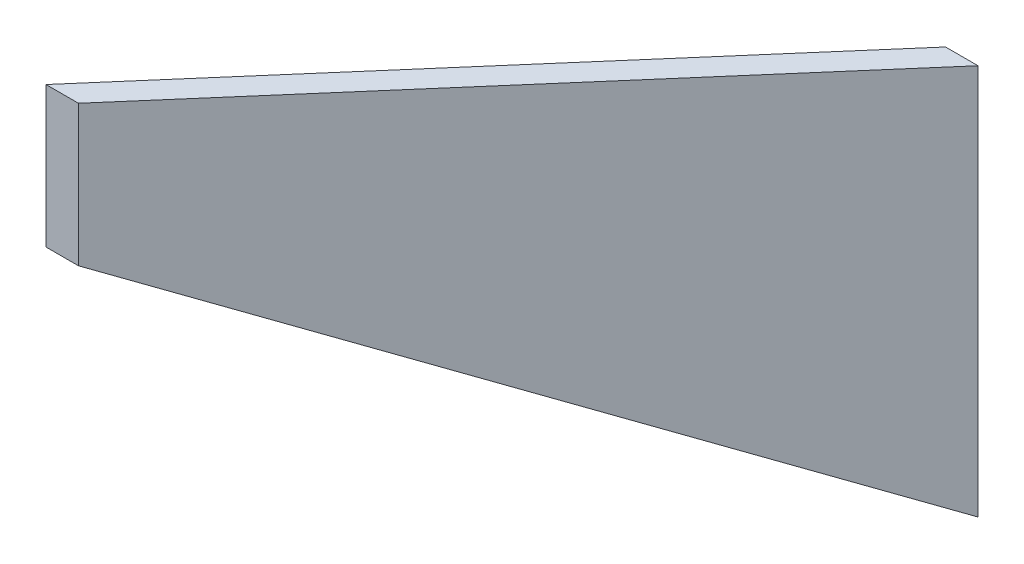
SolidWorks part; units mm, degrees
ref_plane "Front Plane" through (0, 0, 0) normal (0, 0, 1) x (1, 0, 0)
ref_plane "Top Plane" through (0, 0, 0) normal (0, 1, 0) x (1, 0, 0)
ref_plane "Right Plane" through (0, 0, 0) normal (1, 0, 0) x (0, 0, -1)
ref_plane "Plane3" through (0, 0, 127) normal (0, 0, 1) x (1, 0, 0)
ref_plane "Plane1" through (-63.5, 0, 0) normal (1, 0, 0) x (0, 0, -1)
ref_plane "Plane2" through (0, 149.86, 0) normal (0, 1, 0) x (1, 0, 0)
sketch "Sketch2" plane through (0, 0, 0) normal (0, 1, 0) x (1, 0, 0)
  line L0 (-57.15, 0) -> (224.536, 0)
  line L1 (224.536, 0) -> (-24.3577, -163.9616)
  line L2 (-24.3577, -163.9616) -> (-57.15, 0)
  line L3 (0, 0) -> (0, -127) construction
  line L4 (-31.75, -127) -> (31.75, -127) construction
  point P2 (0, 0)
  dimension "D1" = 281.686
  dimension "D2" = 57.15
  dimension "D3" = 63.5
  dimension "D4" = 127
extrude "Boss-Extrude1" add sketch "Sketch2" along normal blind 152.4
sketch "Sketch3" plane through (-63.5, 0, 0) normal (1, 0, 0) x (0, 0, -1)
  line L0 (0, 76.2) -> (-127, 76.2) construction
  line L1 (0, 152.4) -> (0, 0) construction
  line L2 (-127, 44.45) -> (-127, 107.95) construction
  line L3 (0, 152.4) -> (-127, 107.95)
  line L4 (0, 0) -> (-127, 44.45)
  line L5 (-127, 107.95) -> (-217.7143, 76.2)
  line L6 (-127, 44.45) -> (-217.7143, 76.2)
  line L7 (0, 152.4) -> (0, 0)
  point P7 (-127, 76.2)
  dimension "D1" = 127
  dimension "D2" = 63.5
extrude "Cut-Extrude2" cut sketch "Sketch3" along normal through all flip side to cut
shell "Shell1" thickness 6.35
sketch "Sketch8" plane through (0, 0, 127) normal (0, 0, 1) x (1, 0, 0)
  line L1 (-92.1964, -50.8668) -> (173.8662, -50.8668)
  line L2 (-92.1964, -50.8668) -> (-92.1964, 231.3249)
  line L3 (-92.1964, 231.3249) -> (173.8662, 231.3249)
  line L4 (173.8662, -50.8668) -> (173.8662, 231.3249)
extrude "Cut-Extrude6" cut sketch "Sketch8" along normal through all
sketch "Sketch4" plane through (-63.5, 0, 0) normal (1, 0, 0) x (0, 0, -1)
  line L1 (0, 152.4) -> (0, 145.6723)
  line L2 (0, 145.6723) -> (-163.9616, 88.2857)
  line L4 (-163.9616, 64.1143) -> (0, 6.7277)
  line L5 (0, 152.4) -> (-163.9616, 95.0134)
  line L7 (-163.9616, 57.3866) -> (0, 0)
  line L8 (-163.9616, 95.0134) -> (-163.9616, 57.3866) construction
  line L9 (-163.9616, 95.0134) -> (-163.9616, 88.2857)
  line L10 (-163.9616, 64.1143) -> (-163.9616, 57.3866)
  line L11 (0, 152.4) -> (0, 0) construction
  line L12 (0, 0) -> (0, 6.7277)
  line L13 (-127, 107.95) -> (0, 152.4) construction
  line L14 (-127, 44.45) -> (0, 0) construction
extrude "Cut-Extrude3" cut sketch "Sketch4" along normal through all
sketch "Sketch5" plane through (0, 149.86, 0) normal (0, 1, 0) x (1, 0, 0)
  line L0 (-20.1978, -152.3824) -> (-18.6358, -160.1922)
  line L1 (31.75, -127) -> (224.536, 0) construction
  line L2 (-25.2742, -127) -> (-50.6742, 0) construction
  line L3 (-18.6358, -160.1922) -> (344.3171, -160.1922)
  line L4 (344.3171, -160.1922) -> (317.8797, 72.8643)
  line L5 (317.8797, 72.8643) -> (-35.1367, 43.3166)
  line L6 (-35.1367, 43.3166) -> (-20.1978, -152.3824)
  point P2 (-20.1978, -152.3824)
extrude "Cut-Extrude4" cut sketch "Sketch5" against normal through all flip side to cut
ref_plane "Plane4" through (156.5838, 0, -103.1514) normal (-0.8351, 0, 0.5501) x (0, -1, 0)
